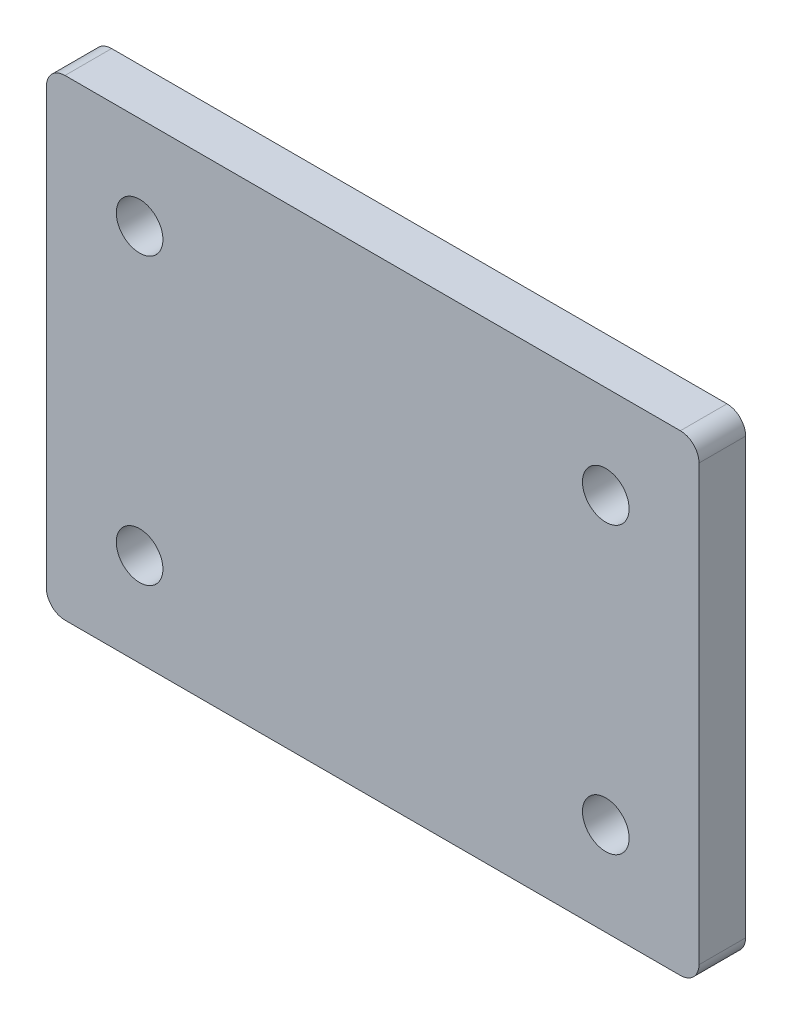
SolidWorks part; units mm, degrees
ref_plane "Front Plane" through (0, 0, 0) normal (0, 0, 1) x (1, 0, 0)
ref_plane "Top Plane" through (0, 0, 0) normal (0, 1, 0) x (1, 0, 0)
ref_plane "Right Plane" through (0, 0, 0) normal (1, 0, 0) x (0, 0, -1)
sketch "Sketch1" plane through (0, 0, 0) normal (0, 0, 1) x (1, 0, 0)
  line L1 (-44.45, -32.1297) -> (44.45, -32.1297)
  line L2 (-44.45, -32.1297) -> (-44.45, 32.1297)
  line L3 (-44.45, 32.1297) -> (44.45, 32.1297)
  line L4 (44.45, -32.1297) -> (44.45, 32.1297)
  line L5 (-44.45, -32.1297) -> (44.45, 32.1297) construction
  line L6 (-44.45, 32.1297) -> (44.45, -32.1297) construction
  point P0 (0, 0)
  dimension "D1" = 88.9
  dimension "D2" = 64.2595
extrude "Boss-Extrude1" add sketch "Sketch1" along normal blind 6.35
fillet "Fillet1" radius 2.54 4 edges at (44.45, -32.1297, 3.175) (-44.45, -32.1297, 3.175) (-44.45, 32.1297, 3.175) (44.45, 32.1297, 3.175)
sketch "Sketch2" plane through (0, 0, 6.35) normal (0, 0, 1) x (1, 0, 0)
  line L0 (41.91, 32.1297) -> (-41.91, 32.1297) construction
  line L1 (-31.75, -19.4297) -> (31.75, -19.4297) construction
  line L2 (-31.75, -19.4297) -> (-31.75, 19.4297) construction
  line L3 (-31.75, 19.4297) -> (31.75, 19.4297) construction
  line L4 (31.75, -19.4297) -> (31.75, 19.4297) construction
  line L5 (-31.75, -19.4297) -> (31.75, 19.4297) construction
  line L6 (-31.75, 19.4297) -> (31.75, -19.4297) construction
  line L7 (44.45, -29.5897) -> (44.45, 29.5897) construction
  circle A0 centre (-31.75, 19.4297) radius 3.175
  circle A1 centre (31.75, 19.4297) radius 3.175
  circle A2 centre (31.75, -19.4297) radius 3.175
  circle A3 centre (-31.75, -19.4297) radius 3.175
  point P0 (0, 0)
  dimension "D3" = 6.35
  dimension "D1" = 12.7
  dimension "D2" = 12.7
extrude "Cut-Extrude1" cut sketch "Sketch2" against normal blind 6.35 contours A0 | A3 | A2 | A1
